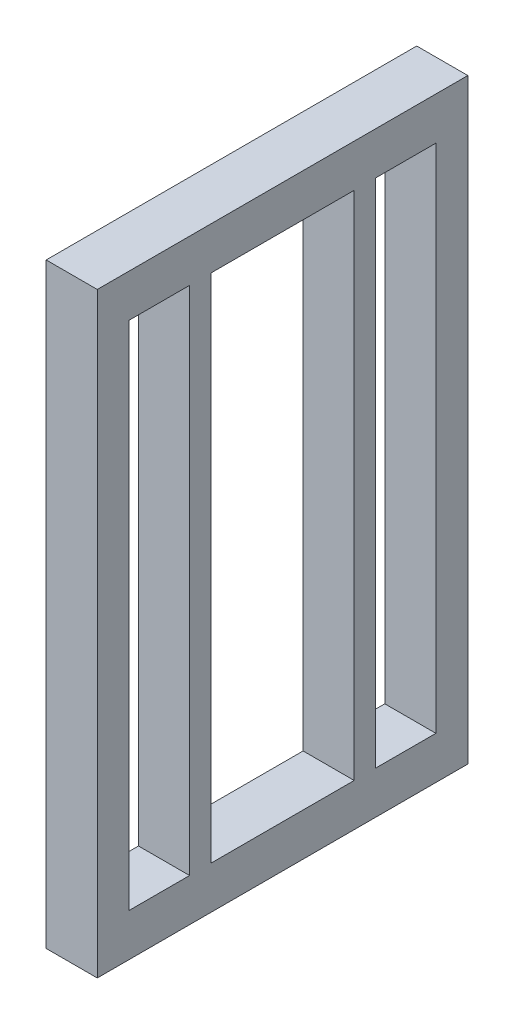
SolidWorks part; units mm, degrees
ref_plane "Front Plane" through (0, 0, 0) normal (0, 0, 1) x (1, 0, 0)
ref_plane "Top Plane" through (0, 0, 0) normal (0, 1, 0) x (1, 0, 0)
ref_plane "Right Plane" through (0, 0, 0) normal (1, 0, 0) x (0, 0, -1)
sketch "Sketch1" plane through (0, 0, 0) normal (0, 1, 0) x (1, 0, 0)
  line L1 (-2.4738, 30.0674) -> (2.3262, 30.0674)
  line L2 (-2.4738, 30.0674) -> (-2.4738, -4.7326)
  line L3 (-2.4738, -4.7326) -> (2.3262, -4.7326)
  line L4 (2.3262, 30.0674) -> (2.3262, -4.7326)
  dimension "D1" = 4.8
  dimension "D2" = 34.8
extrude "Boss-Extrude1" add sketch "Sketch1" along normal blind 56
sketch "Sketch2" plane through (2.3262, 0, 0) normal (1, 0, 0) x (0, 0, -1)
  line L0 (-4.7326, 56) -> (30.0674, 56) construction
  line L1 (-1.7326, 52) -> (27.0674, 52)
  line L2 (-1.7326, 52) -> (-1.7326, 4)
  line L3 (-1.7326, 4) -> (27.0674, 4)
  line L4 (27.0674, 52) -> (27.0674, 4)
  line L5 (-4.7326, 0) -> (30.0674, 0) construction
  line L6 (-4.7326, 56) -> (-4.7326, 0) construction
  line L7 (30.0674, 56) -> (30.0674, 0) construction
  line L8 (3.9374, 52) -> (3.9374, 4)
  line L9 (5.9374, 52) -> (5.9374, 4)
  line L10 (3.9374, 52) -> (5.9374, 52)
  line L11 (3.9374, 4) -> (5.9374, 4)
  line L12 (19.3974, 4) -> (21.3974, 4)
  line L13 (21.3974, 52) -> (21.3974, 4)
  line L14 (19.3974, 52) -> (21.3974, 52)
  line L15 (19.3974, 52) -> (19.3974, 4)
  dimension "D1" = 4
  dimension "D2" = 4
  dimension "D3" = 3
  dimension "D4" = 3
  dimension "D5" = 2
  dimension "D7" = 5.67
  dimension "D8" = 5.67
  dimension "D6" = 2
extrude "Cut-Extrude1" cut sketch "Sketch2" against normal blind 56 contours L8 L1 L2 L3 | L15 L1 L9 L3 | L1 L13 L3 L4
